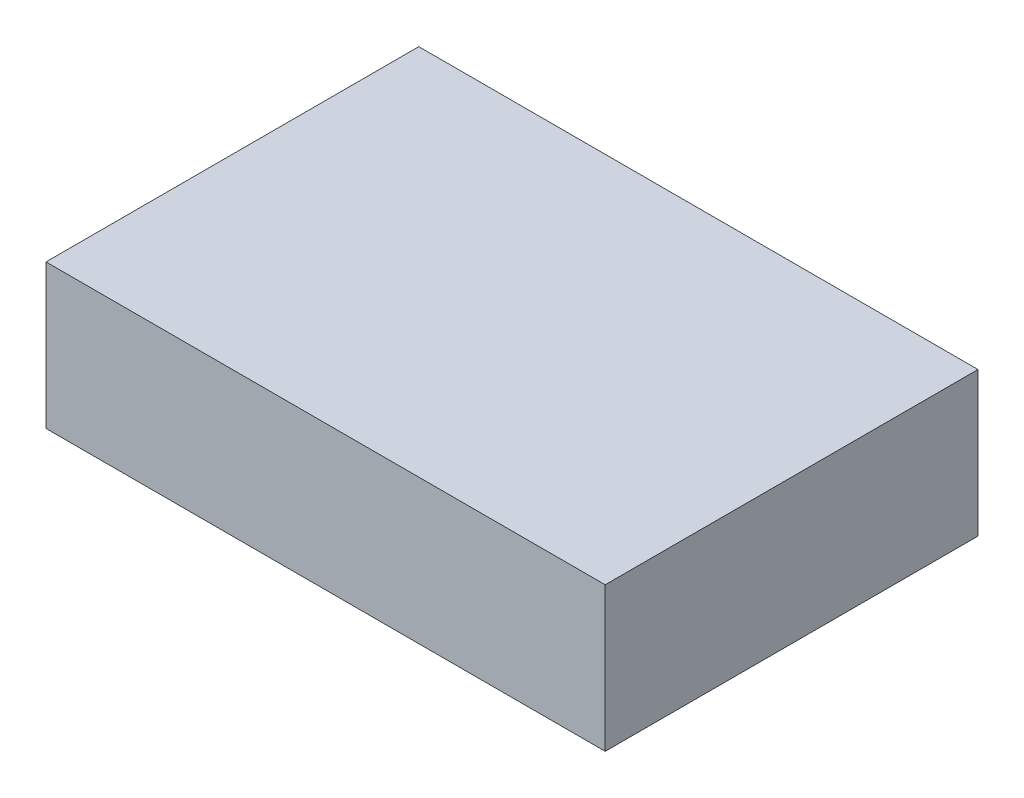
SolidWorks part; units mm, degrees
ref_plane "Front Plane" through (0, 0, 0) normal (0, 0, 1) x (1, 0, 0)
ref_plane "Top Plane" through (0, 0, 0) normal (0, 1, 0) x (1, 0, 0)
ref_plane "Right Plane" through (0, 0, 0) normal (1, 0, 0) x (0, 0, -1)
sketch "Sketch1" plane through (0, 0, 0) normal (0, 1, 0) x (1, 0, 0)
  line L1 (38.1, -25.4) -> (-38.1, -25.4)
  line L2 (38.1, -25.4) -> (38.1, 25.4)
  line L3 (38.1, 25.4) -> (-38.1, 25.4)
  line L4 (-38.1, -25.4) -> (-38.1, 25.4)
  line L5 (38.1, -25.4) -> (-38.1, 25.4) construction
  line L6 (38.1, 25.4) -> (-38.1, -25.4) construction
  point P0 (0, 0)
  dimension "D1" = 76.2
  dimension "D2" = 50.8
extrude "Boss-Extrude1" add sketch "Sketch1" along normal blind 19.6596
sketch "Sketch2" plane through (0, 0, 0) normal (0, -1, 0) x (-1, 0, 0)
  circle A0 centre (0, 0) radius 2.54
  dimension "D1" = 5.08
extrude "Boss-Extrude2" add sketch "Sketch2" along normal blind 6.35
